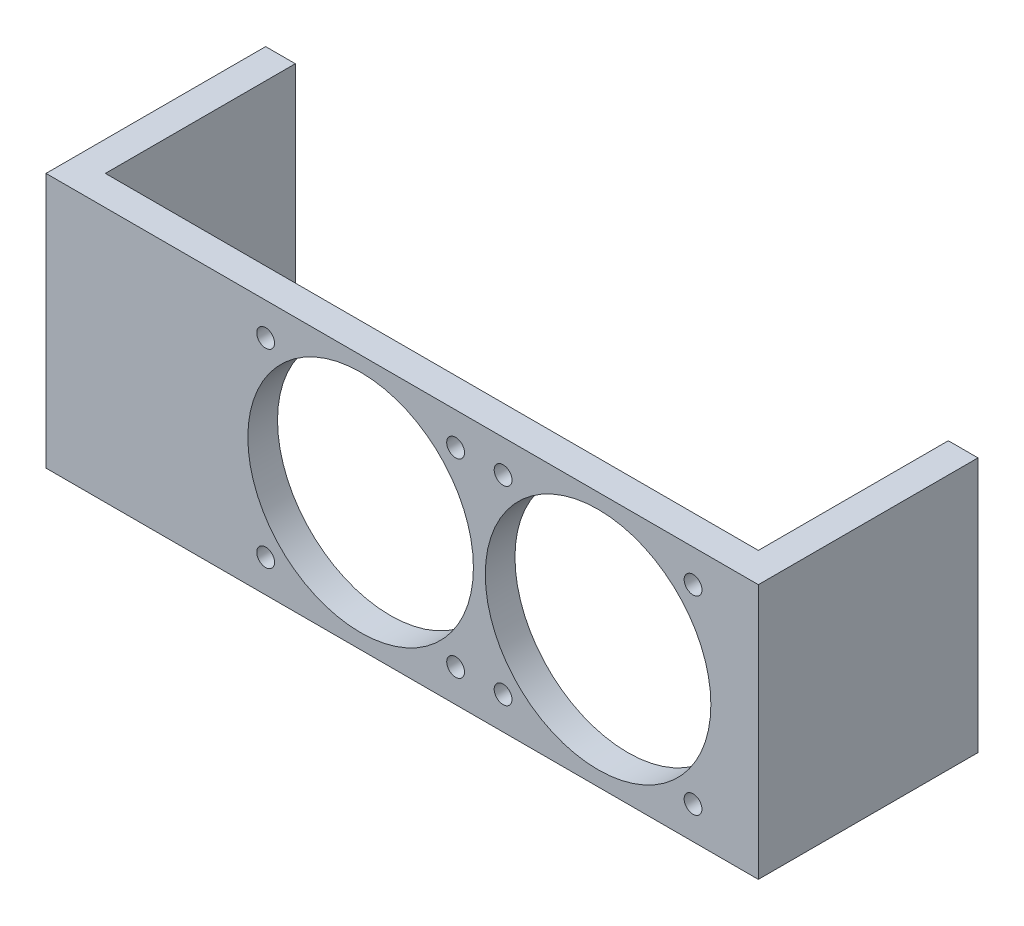
SolidWorks part; units mm, degrees
ref_plane "前视基准面" through (0, 0, 0) normal (0, 0, 1) x (1, 0, 0)
ref_plane "上视基准面" through (0, 0, 0) normal (0, 1, 0) x (1, 0, 0)
ref_plane "右视基准面" through (0, 0, 0) normal (1, 0, 0) x (0, 0, -1)
sketch "草图1" plane through (0, 0, 0) normal (0, 0, 1) x (1, 0, 0)
  line L0 (80.6147, 4.2541) -> (78.6147, 4.2541) construction
  line L1 (-29.3853, 25.7541) -> (80.6147, 25.7541)
  line L2 (-29.3853, 25.7541) -> (-29.3853, -17.2459)
  line L3 (-29.3853, -17.2459) -> (80.6147, -17.2459)
  line L4 (80.6147, 25.7541) -> (80.6147, -17.2459)
  line L5 (78.6147, 4.2541) -> (58.6147, 4.2541) construction
  line L6 (74.6147, 20.2541) -> (74.6147, -11.7459)
  line L7 (58.6147, 25.7541) -> (58.6147, -17.2459) construction
  line L8 (58.6147, 4.2541) -> (38.6147, 4.2541) construction
  line L9 (38.6147, 25.7541) -> (38.6147, -17.2459)
  circle A0 centre (58.6147, 4.2541) radius 19
  circle A1 centre (74.6147, 20.2541) radius 1.5
  circle A2 centre (74.6147, -11.7459) radius 1.5
  circle A3 centre (42.6147, -11.7459) radius 1.5
  circle A4 centre (42.6147, 20.2541) radius 1.5
  circle A5 centre (34.6147, -11.7459) radius 1.5
  circle A6 centre (2.6147, -11.7459) radius 1.5
  circle A7 centre (2.6147, 20.2541) radius 1.5
  circle A8 centre (34.6147, 20.2541) radius 1.5
  circle A9 centre (18.6147, 4.2541) radius 19
  point P8 (74.6147, 4.2541)
  point P12 (74.6147, 4.2541)
  point P25 (38.6147, 4.2541)
  dimension "D5" = 16
  dimension "D7" = 20
  dimension "D1" = 110
  dimension "D2" = 43
  dimension "D3" = 2
  dimension "D4" = 20
  dimension "D6" = 32
extrude "凸台-拉伸2" add sketch "草图1" along normal blind 5
sketch "草图2" plane through (0, 0, 5) normal (0, 0, 1) x (1, 0, 0)
  line L1 (80.6147, 25.7541) -> (85.6147, 25.7541)
  line L2 (80.6147, 25.7541) -> (80.6147, -17.2459)
  line L3 (80.6147, -17.2459) -> (85.6147, -17.2459)
  line L4 (85.6147, 25.7541) -> (85.6147, -17.2459)
  line L5 (-29.3853, 25.7541) -> (-34.3853, 25.7541)
  line L6 (-29.3853, 25.7541) -> (-29.3853, -17.2459)
  line L7 (-29.3853, -17.2459) -> (-34.3853, -17.2459)
  line L8 (-34.3853, 25.7541) -> (-34.3853, -17.2459)
  dimension "D1" = 43
  dimension "D2" = 43
  dimension "D3" = 5
  dimension "D4" = 5
extrude "凸台-拉伸4" add sketch "草图2" against normal blind 37
